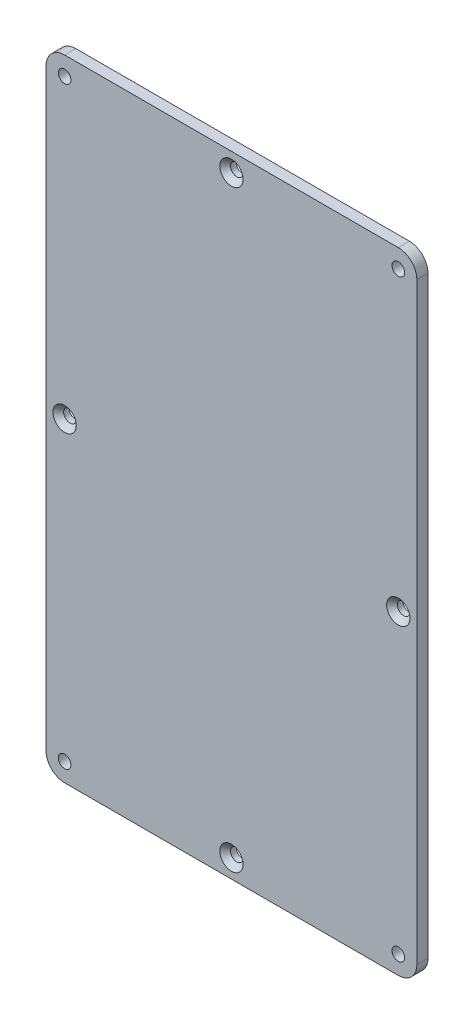
SolidWorks part; units mm, degrees
ref_plane "Front Plane" through (0, 0, 0) normal (0, 0, 1) x (1, 0, 0)
ref_plane "Top Plane" through (0, 0, 0) normal (0, 1, 0) x (1, 0, 0)
ref_plane "Right Plane" through (0, 0, 0) normal (1, 0, 0) x (0, 0, -1)
sketch "Sketch1" plane through (0, 0, 0) normal (0, 0, 1) x (1, 0, 0)
  line L1 (0, 0) -> (100, 0)
  line L2 (0, 0) -> (0, 170)
  line L3 (0, 170) -> (100, 170)
  line L4 (100, 0) -> (100, 170)
  dimension "D1" = 100
  dimension "D2" = 170
extrude "Boss-Extrude1" add sketch "Sketch1" along normal blind 3
hole_wizard "M3 Clearance Hole1" positions "Sketch4" profile "Sketch5" hole size "M3" standard "ANSI Metric"
sketch "Sketch4" plane through (0, 0, 3) normal (0, 0, 1) x (1, 0, 0)
  line L0 (5, 165) -> (5, 85) construction
  line L1 (5, 85) -> (5, 5) construction
  line L2 (5, 5) -> (50, 5) construction
  line L3 (50, 5) -> (95, 5) construction
  line L4 (95, 5) -> (95, 85) construction
  line L5 (95, 85) -> (95, 165) construction
  line L6 (95, 165) -> (50, 165) construction
  line L7 (50, 165) -> (5, 165) construction
  line L10 (0, 170) -> (0, 0) construction
  line L11 (100, 170) -> (0, 170) construction
  line L12 (100, 0) -> (100, 170) construction
  line L13 (0, 0) -> (100, 0) construction
  point P0 (5, 165)
  point P4 (95, 165)
  point P8 (95, 5)
  point P12 (5, 5)
  dimension "D1" = 5
  dimension "D2" = 5
  dimension "D3" = 5
  dimension "D4" = 5
sketch "Sketch5" plane through (5, 165, 3) normal (1, 0, 0) x (0, -1, 0)
  line L0 (0, 0) -> (0, 8.5215)
  line L1 (0, 8.5215) -> (1.7, 7.5)
  line L2 (1.7, 7.5) -> (1.7, 0)
  line L5 (1.7, 0) -> (0, 0)
  line L10 (0, 8.5215) -> (-1.7, 7.5) construction
  line L11 (0, -6.35) -> (0, 107.95) construction
  dimension "Hole Dia." = 3.4
  dimension "Hole Depth" = 7.5
  dimension "Drill Angle" = 118
fillet "Fillet1" radius 5 4 edges at (100, 170, 1.5) (100, 0, 1.5) (0, 0, 1.5) (0, 170, 1.5)
hole_wizard "CSK for M3 Flat Head Machine Screw1" positions "Sketch6" profile "Sketch7" countersink size "M3" standard "ANSI Metric"
sketch "Sketch6" plane through (0, 0, 3) normal (0, 0, 1) x (1, 0, 0)
  line L0 (100, 5) -> (100, 165) construction
  line L1 (0, 165) -> (0, 5) construction
  line L2 (95, 170) -> (5, 170) construction
  line L3 (5, 0) -> (95, 0) construction
  point P0 (50, 165)
  point P2 (50, 5)
  point P4 (95, 85)
  point P6 (5, 85)
  point P17 (50, 0)
  point P18 (0, 85)
  dimension "D1" = 5
  dimension "D2" = 5
  dimension "D3" = 5
  dimension "D4" = 5
sketch "Sketch7" plane through (50, 165, 3) normal (1, 0, 0) x (0, -1, 0)
  line L0 (0, 0) -> (0, 8.5215)
  line L1 (0, 8.5215) -> (1.7, 7.5)
  line L2 (1.7, 7.5) -> (1.7, 1.45)
  line L3 (1.7, 1.45) -> (3.15, 0)
  line L5 (3.15, 0) -> (0, 0)
  line L6 (-1.7, 1.45) -> (-3.15, 0) construction
  line L10 (0, 8.5215) -> (-1.7, 7.5) construction
  line L11 (0, -6.35) -> (0, 107.95) construction
  dimension "Hole Dia." = 3.4
  dimension "Hole Depth" = 7.5
  dimension "Near C'Sink Dia." = 6.3
  dimension "Near C'Sink Angle" = 90
  dimension "Drill Angle" = 118
